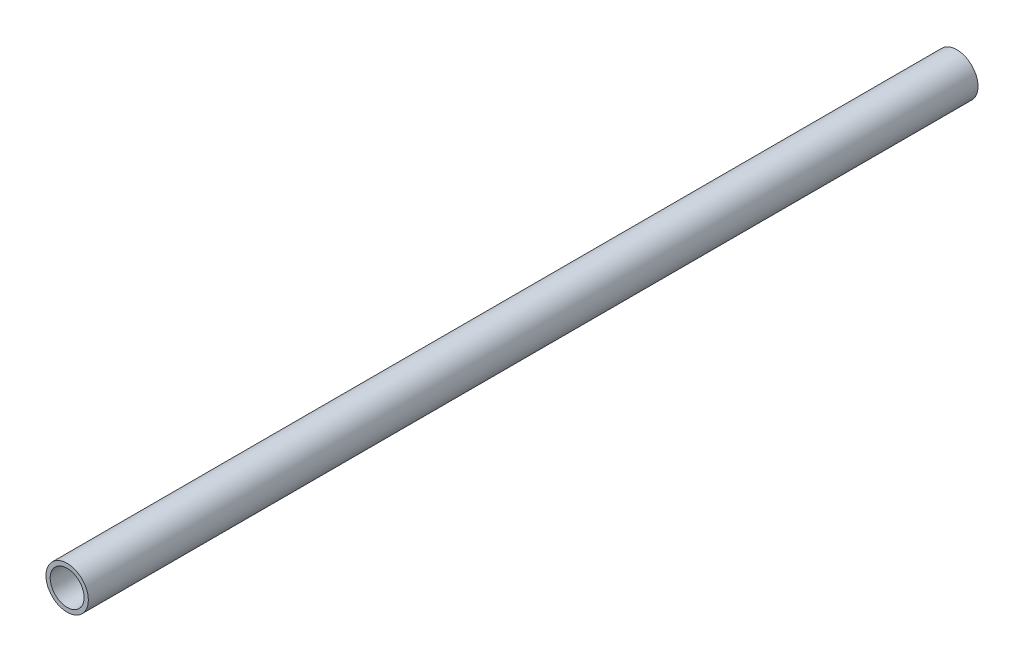
SolidWorks part; units mm, degrees
ref_plane "前视基准面" through (0, 0, 0) normal (0, 0, 1) x (1, 0, 0)
ref_plane "上视基准面" through (0, 0, 0) normal (0, 1, 0) x (1, 0, 0)
ref_plane "右视基准面" through (0, 0, 0) normal (1, 0, 0) x (0, 0, -1)
other "Configuration Table"
sketch "草图1" plane through (0, 0, 0) normal (0, 0, 1) x (1, 0, 0)
  circle A0 centre (0, 0) radius 5
  dimension "D1" = 10
extrude "凸台-拉伸1" add sketch "草图1" along normal blind 210
shell "抽壳1" thickness 1
sketch "草图2" plane through (0, 0, 1) normal (0, 0, 1) x (1, 0, 0)
  circle A1 centre (0, 0) radius 4
  circle A2 centre (0, 0) radius 4
  dimension "D1" = 0
extrude "切除-拉伸1" cut sketch "草图2" against normal up to next
